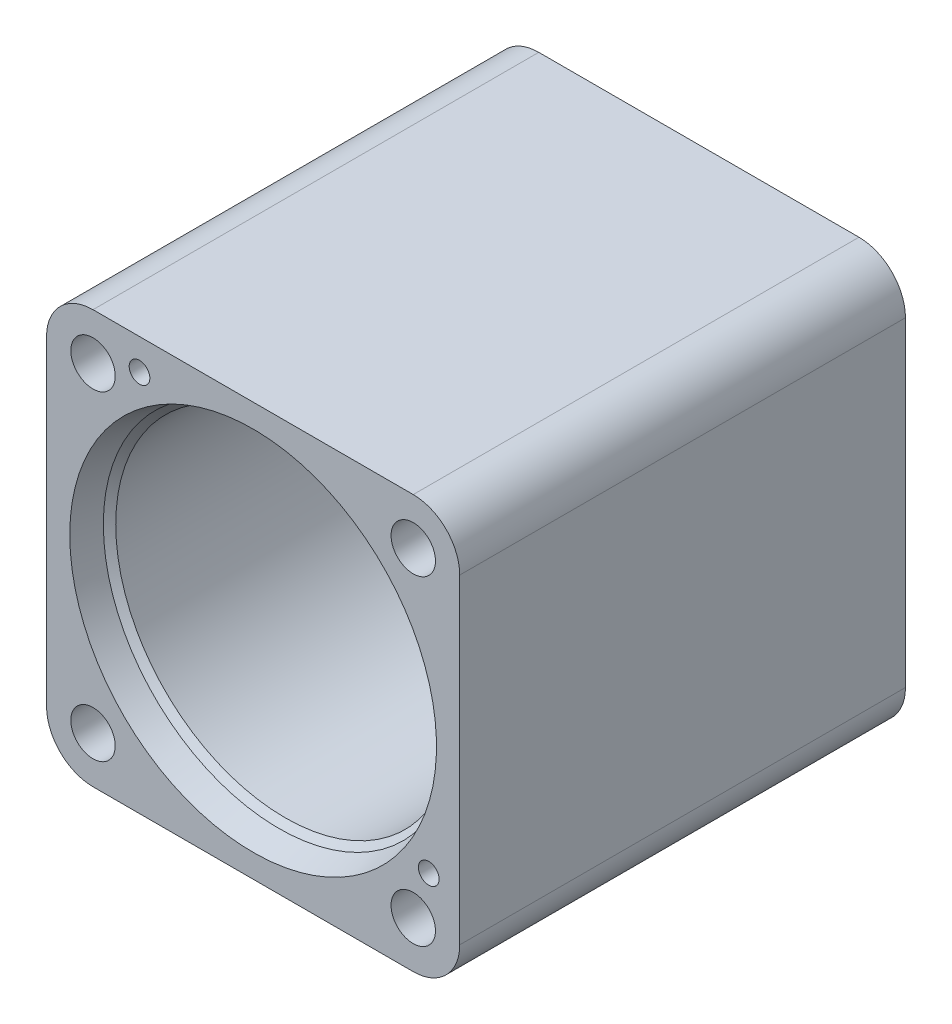
SolidWorks part; units mm, degrees
ref_plane "Front Plane" through (0, 0, 0) normal (0, 0, 1) x (1, 0, 0)
ref_plane "Top Plane" through (0, 0, 0) normal (0, 1, 0) x (1, 0, 0)
ref_plane "Right Plane" through (0, 0, 0) normal (1, 0, 0) x (0, 0, -1)
sketch "Sketch1" plane through (0, 0, 0) normal (0, 0, 1) x (1, 0, 0)
  line L1 (-15.5, -20) -> (15.5, -20)
  line L2 (-20, -15.5) -> (-20, 15.5)
  line L3 (-15.5, 20) -> (15.5, 20)
  line L4 (20, -15.5) -> (20, 15.5)
  line L5 (-20, -20) -> (20, 20) construction
  line L6 (-20, 20) -> (20, -20) construction
  circle A0 centre (0, 0) radius 17.75 construction
  circle A1 centre (0, 0) radius 16.4
  arc A2 (-15.5, -20) -> (-20, -15.5) centre (-15.5, -15.5) cw
  arc A3 (15.5, -20) -> (20, -15.5) centre (15.5, -15.5) ccw
  arc A4 (15.5, 20) -> (20, 15.5) centre (15.5, 15.5) cw
  arc A5 (-20, 15.5) -> (-15.5, 20) centre (-15.5, 15.5) cw
  circle A6 centre (-15.5, 15.5) radius 2.15
  circle A7 centre (15.5, 15.5) radius 2.15
  circle A8 centre (15.5, -15.5) radius 2.15
  circle A9 centre (-15.5, -15.5) radius 2.15
  point P0 (0, 0)
  point P31 (0, 0)
  dimension "D3" = 35.5
  dimension "D4" = 32.8
  dimension "D5" = 4.5
  dimension "D6" = 4.3
  dimension "D1" = 40
  dimension "D2" = 40
  dimension "D7" = 4
extrude "Boss-Extrude1" add sketch "Sketch1" along normal blind 43.15
sketch "Sketch5" plane through (0, 0, 0) normal (0, 1, 0) x (1, 0, 0)
  line L0 (0, -3.1) -> (16.4, -3.1) construction
  line L1 (16.4, -3.1) -> (17, -2.5)
  line L2 (17, -2.5) -> (17.75, 0)
  line L3 (20, 0) -> (15.5, 0) construction
  line L4 (16.4, -3.1) -> (16.4, 0)
  line L5 (16.4, 0) -> (-16.4, 0) construction
  line L6 (17.65, 0) -> (13.35, 0) construction
  line L7 (16.4, 0) -> (17.75, 0)
  dimension "D1" = 0.6
  dimension "D2" = 16.4
  dimension "D3" = 0.6
  dimension "D4" = 2.5
  dimension "D5" = 0.75
ref_axis "Axis1" through (0, 0, -2.15) along (0, 0, 1)
revolve "Cut-Revolve1" cut sketch "Sketch5" angle 360 about axis through (0, 0, -2.15) along (0, 0, 1)
ref_plane "Plane1" through (0, 0, 21.575) normal (0, 0, -1) x (-1, 0, 0)
mirror "Mirror1" about plane through (0, 0, 21.575) normal (0, 0, -1) of "Cut-Revolve1"
sketch "Sketch6" plane through (0, 0, 43.15) normal (0, 0, 1) x (1, 0, 0)
  line L0 (-20, 15.5) -> (-20, -15.5) construction
  line L1 (-15.5, -20) -> (15.5, -20) construction
  line L2 (-18.682, -18.682) -> (18.682, 18.682) construction
  circle A0 centre (-11, 17) radius 1
  arc A1 (-20, -15.5) -> (-15.5, -20) centre (-15.5, -15.5) ccw construction
  arc A2 (20, 15.5) -> (15.5, 20) centre (15.5, 15.5) ccw construction
  circle A3 centre (17, -11) radius 1
  dimension "D2" = 2
  dimension "D1" = 9
  dimension "D3" = 37
extrude "Cut-Extrude1" cut sketch "Sketch6" against normal blind 5
